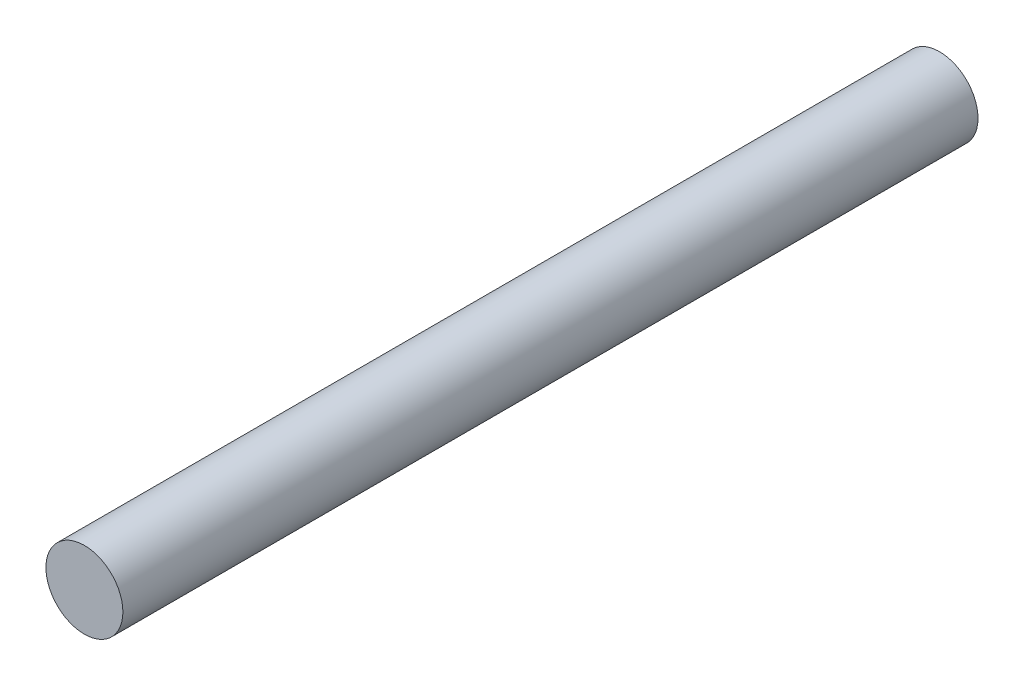
SolidWorks part; units mm, degrees
ref_plane "Plan de face" through (0, 0, 0) normal (0, 0, 1) x (1, 0, 0)
ref_plane "Plan de dessus" through (0, 0, 0) normal (0, 1, 0) x (1, 0, 0)
ref_plane "Plan de droite" through (0, 0, 0) normal (1, 0, 0) x (0, 0, -1)
sketch "Esquisse2" plane through (0, 0, 0) normal (0, 0, 1) x (1, 0, 0)
  circle A0 centre (0, 0) radius 2
  dimension "D1" = 4
extrude "Boss.-Extru.1" add sketch "Esquisse2" along normal mid plane 44.45
